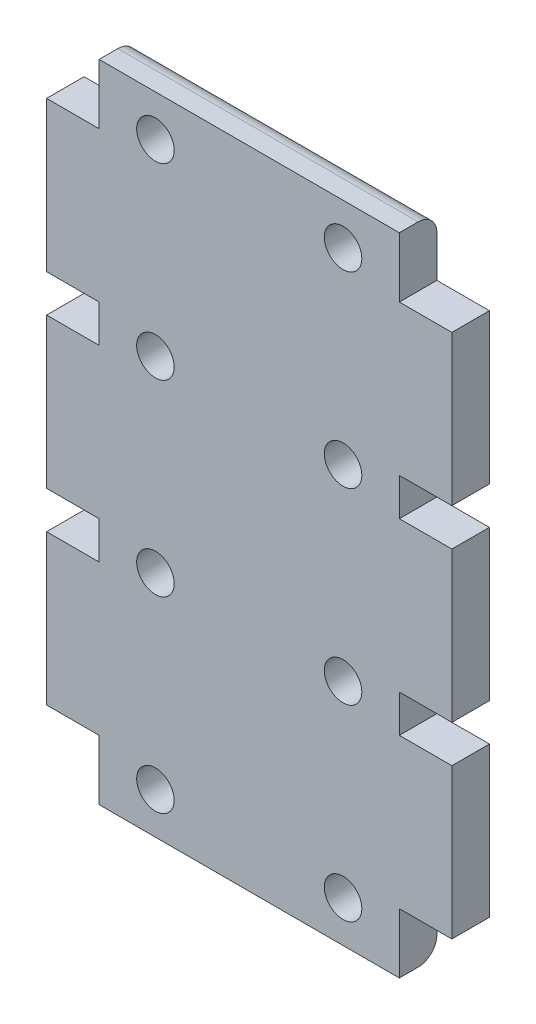
SolidWorks part; units mm, degrees
material "ABS"
ref_plane "Front Plane" through (0, 0, 0) normal (0, 0, 1) x (1, 0, 0)
ref_plane "Top Plane" through (0, 0, 0) normal (0, 1, 0) x (1, 0, 0)
ref_plane "Right Plane" through (0, 0, 0) normal (1, 0, 0) x (0, 0, -1)
sketch "Sketch1" plane through (0, 0, 0) normal (0, 0, 1) x (1, 0, 0)
  line L0 (-50, 20) -> (-60, 20)
  line L1 (0, 0) -> (-10, 0)
  line L2 (0, 0) -> (0, 20)
  line L3 (0, 20) -> (-10, 20)
  line L4 (-60, 0) -> (-60, 20)
  line L6 (-50, 20) -> (-50, 28)
  line L7 (-50, 28) -> (-10, 28)
  line L8 (-10, 20) -> (-10, 28)
  line L10 (-50, 0) -> (-50, -5)
  line L12 (-10, 0) -> (-10, -5)
  line L13 (-50, 0) -> (-60, 0)
  line L15 (0, -5) -> (-10, -5)
  line L16 (0, -5) -> (0, -25)
  line L17 (0, -25) -> (-10, -25)
  line L18 (-60, -5) -> (-60, -25)
  line L20 (-10, -25) -> (-10, -30)
  line L22 (-50, -25) -> (-50, -30)
  line L23 (0, -30) -> (-10, -30)
  line L24 (0, -30) -> (0, -50)
  line L25 (0, -50) -> (-10, -50)
  line L26 (-60, -30) -> (-60, -50)
  line L28 (-10, -50) -> (-10, -58)
  line L29 (-10, -58) -> (-50, -58)
  line L30 (-50, -50) -> (-50, -58)
  line L31 (-50, -5) -> (-60, -5)
  line L33 (-50, -25) -> (-60, -25)
  line L34 (-50, -50) -> (-60, -50)
  line L35 (-50, -30) -> (-60, -30)
  circle A0 centre (-42.5, 22.5) radius 2.5
  circle A1 centre (-17.5, 22.5) radius 2.5
  circle A2 centre (-42.5, -2.5) radius 2.5
  circle A3 centre (-17.5, -2.5) radius 2.5
  circle A4 centre (-17.5, -27.5) radius 2.5
  circle A5 centre (-42.5, -27.5) radius 2.5
  circle A6 centre (-17.5, -52.5) radius 2.5
  circle A7 centre (-42.5, -52.5) radius 2.5
  point P21 (-10, 24)
  point P38 (-10, -54)
  dimension "D9" = 5
  dimension "D10" = 5
  dimension "D11" = 5
  dimension "D12" = 5
  dimension "D13" = 7.5
  dimension "D14" = 7.5
  dimension "D16" = 7.5
  dimension "D17" = 2.5
  dimension "D19" = 2.5
  dimension "D20" = 2.5
  dimension "D35" = 5
  dimension "D36" = 5
  dimension "D37" = 5
  dimension "D38" = 5
  dimension "D39" = 7.5
  dimension "D41" = 7.5
  dimension "D43" = 2.5
  dimension "D44" = 7.5
  dimension "D45" = 7.5
  dimension "D46" = 2.5
  dimension "D1" = 60
  dimension "D2" = 20
  dimension "D3" = 40
  dimension "D4" = 10
  dimension "D5" = 10
  dimension "D6" = 40
  dimension "D7" = 8
  dimension "D8" = 5
  dimension "D15" = 2.5
  dimension "D18" = 7.5
  dimension "D21" = 20
  dimension "D23" = 60
  dimension "D24" = 10
  dimension "D25" = 10
  dimension "D26" = 40
  dimension "D27" = 5
  dimension "D28" = 20
  dimension "D30" = 10
  dimension "D31" = 60
  dimension "D32" = 10
  dimension "D33" = 40
  dimension "D34" = 8
extrude "Boss-Extrude1" add sketch "Sketch1" along normal blind 5
fillet "Fillet1" radius 2.5 1 edges at (-30, -58, 0)
fillet "Fillet2" radius 2.5 1 edges at (-30, 28, 0)
sketch "Sketch2" plane through (0, 0, 0) normal (0, 0, -1) x (-1, 0, 0)
  line L8 (50, 20) -> (60, 20) construction
  line L9 (60, -50) -> (57, -50)
  line L10 (60, -50) -> (60, 20)
  line L11 (60, 20) -> (57, 20)
  line L12 (57, -50) -> (57, 20)
  line L13 (10, -50) -> (0, -50) construction
  line L14 (0, 20) -> (3, 20)
  line L15 (0, 20) -> (0, -50)
  line L16 (0, -50) -> (3, -50)
  line L17 (3, 20) -> (3, -50)
  dimension "D1" = 3
  dimension "D2" = 3
extrude "Cut-Extrude3" cut sketch "Sketch2" against normal blind 10
